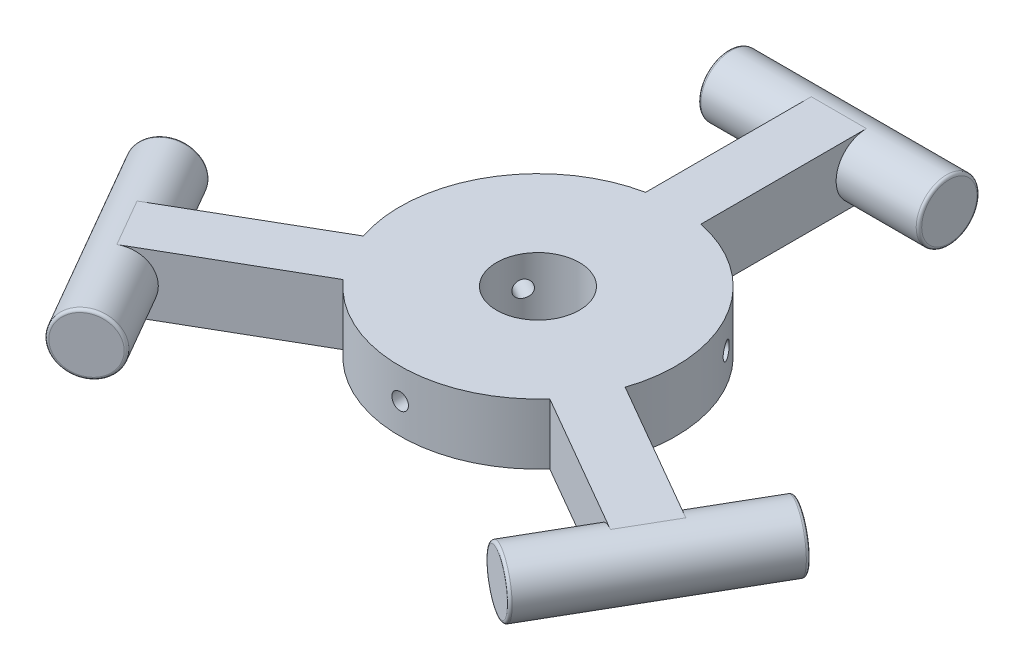
SolidWorks part; units mm, degrees
ref_plane "Front Plane" through (0, 0, 0) normal (0, 0, 1) x (1, 0, 0)
ref_plane "Top Plane" through (0, 0, 0) normal (0, 1, 0) x (1, 0, 0)
ref_plane "Right Plane" through (0, 0, 0) normal (1, 0, 0) x (0, 0, -1)
sketch "Sketch1" plane through (0, 0, 0) normal (0, 1, 0) x (1, 0, 0)
  line L0 (0, 54.4949) -> (0, -45.6684) construction
  line L1 (5, 54.4949) -> (-5, 54.4949)
  line L2 (-5, 54.4949) -> (-5, 24.4949)
  line L3 (5, 24.4949) -> (5, 54.4949)
  line L4 (18.7132, -16.5776) -> (44.694, -31.5776)
  line L5 (44.694, -31.5776) -> (49.694, -22.9173)
  line L6 (49.694, -22.9173) -> (23.7132, -7.9173)
  line L7 (-23.7132, -7.9173) -> (-49.694, -22.9173)
  line L8 (-49.694, -22.9173) -> (-44.694, -31.5776)
  line L9 (-44.694, -31.5776) -> (-18.7132, -16.5776)
  circle A0 centre (0, 0) radius 7.5
  circle A1 centre (0, 0) radius 25
  arc A3 (-5, 24.4949) -> (5, 24.4949) centre (0, 0) cw
  arc A4 (23.7132, -7.9173) -> (18.7132, -16.5776) centre (0, 0) cw
  arc A5 (-18.7132, -16.5776) -> (-23.7132, -7.9173) centre (0, 0) cw
  point P22 (0, 0)
  dimension "D1" = 15
  dimension "D2" = 50
  dimension "D3" = 10
  dimension "D4" = 5
  dimension "D5" = 30
  dimension "D6" = 3
extrude "Boss-Extrude1" add sketch "Sketch1" along normal blind 11 contours A1 L0 A0 | L0 A3 A1 A0 | L1 L0 A1 L3 | L0 L1 L2 A3 | A1 L4 L5 L6 | A1 L7 L8 L9
sketch "Sketch2" plane through (47.194, 0, 27.2474) normal (0.866, 0, 0.5) x (0.5, 0, -0.866)
  line L0 (-19.5, 0) -> (19.5, 0)
  line L2 (20, 0.5) -> (20, 5.5)
  line L6 (20, 5.5) -> (-20, 5.5)
  line L9 (-20, 5.5) -> (-20, 0.5)
  arc A0 (19.5, 0) -> (20, 0.5) centre (19.5, 0.5) ccw
  arc A4 (-20, 0.5) -> (-19.5, 0) centre (-19.5, 0.5) ccw
  point P4 (0, 0)
  point P7 (20, 5.5)
  point P9 (-20, 5.5)
  dimension "D6" = 0.5
  dimension "D7" = 0.5
  dimension "D1" = 40
  dimension "D10" = 5.5
revolve "Revolve1" add sketch "Sketch2" angle 360 about L6
pattern_circular "CirPattern1" count 3 every 120 about axis through (0, 0, 0) along (0, 1, 0) of "Revolve1"
ref_plane "Plane2" through (0, 0, 25) normal (0, 0, 1) x (1, 0, 0)
sketch "Sketch4" plane through (0, 0, 25) normal (0, 0, 1) x (1, 0, 0)
  circle A0 centre (0, 5.5) radius 1.5
  dimension "D1" = 3
  dimension "D2" = 5.5
extrude "Cut-Extrude1" cut sketch "Sketch4" against normal blind 20
pattern_circular "CirPattern3" count 3 every 120 about axis through (0, 11, 0) along (0, 1, 0) of "Cut-Extrude1"
